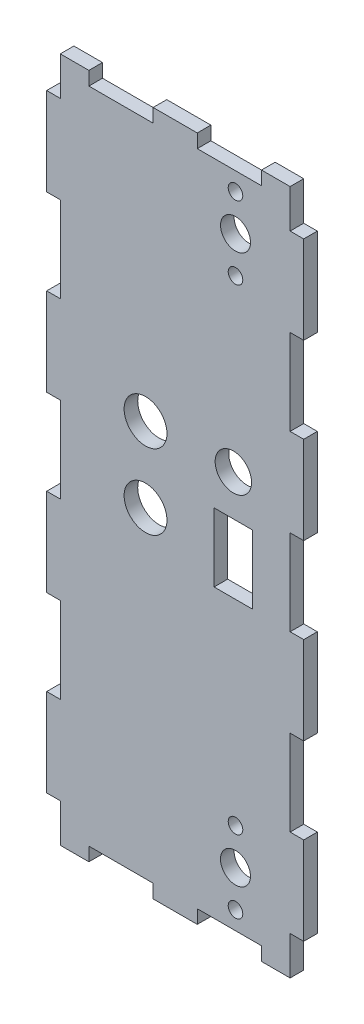
SolidWorks part; units mm, degrees
ref_plane "Front Plane" through (0, 0, 0) normal (0, 0, 1) x (1, 0, 0)
ref_plane "Top Plane" through (0, 0, 0) normal (0, 1, 0) x (1, 0, 0)
ref_plane "Right Plane" through (0, 0, 0) normal (1, 0, 0) x (0, 0, -1)
sketch "Sketch1" plane through (0, 0, 0) normal (0, 0, 1) x (1, 0, 0)
  line L1 (3.175, -25.5685) -> (-56.825, -25.5685)
  line L2 (3.175, -25.5685) -> (3.175, 134.4315)
  line L3 (3.175, 134.4315) -> (-56.825, 134.4315)
  line L4 (-56.825, -25.5685) -> (-56.825, 134.4315)
  dimension "D1" = 160
  dimension "D2" = 60
extrude "Boss-Extrude1" add sketch "Sketch1" against normal up to surface (3.175 mm away)
sketch "Sketch4" plane through (0, 0, 0) normal (0, 0, 1) x (1, 0, 0)
  line L0 (3.175, 134.4315) -> (-56.825, 134.4315) construction
  line L1 (-56.825, 134.4315) -> (-56.825, -25.5685) construction
  line L2 (-56.825, -25.5685) -> (3.175, -25.5685) construction
  line L3 (3.175, -25.5685) -> (0, -25.5685)
  line L4 (0, -25.5685) -> (0, -16.5685)
  line L5 (0, -16.5685) -> (3.175, -16.5685)
  line L6 (3.175, 3.9315) -> (0, 3.9315)
  line L7 (0, 24.1815) -> (0, 3.6815) construction
  line L8 (0, 3.9315) -> (0, 23.9315)
  line L9 (0, 23.9315) -> (3.175, 23.9315)
  line L10 (3.175, 44.4315) -> (0, 44.4315)
  line L11 (0, 64.6815) -> (0, 44.1815) construction
  line L12 (0, 44.4315) -> (0, 64.4315)
  line L13 (0, 64.4315) -> (3.175, 64.4315)
  line L14 (3.175, 84.9315) -> (0, 84.9315)
  line L15 (0, 105.1815) -> (0, 84.6815) construction
  line L16 (0, 84.9315) -> (0, 104.9315)
  line L17 (0, 104.9315) -> (3.175, 104.9315)
  line L18 (3.175, 125.4315) -> (0, 125.4315)
  line L19 (0, 134.4315) -> (0, 125.1815) construction
  line L40 (-31.975, -25.5685) -> (-46.975, -25.5685)
  line L41 (-31.975, -25.5685) -> (-31.975, -22.3935)
  line L42 (0, 125.4315) -> (0, 134.4315)
  line L43 (0, 134.4315) -> (3.175, 134.4315)
  line L45 (3.175, -25.5685) -> (3.175, -16.5685)
  line L46 (3.175, 125.4315) -> (3.175, 134.4315)
  line L47 (3.175, 84.9315) -> (3.175, 104.9315)
  line L48 (3.175, 44.4315) -> (3.175, 64.4315)
  line L49 (3.175, 3.9315) -> (3.175, 23.9315)
  line L58 (-26.825, 134.4315) -> (-26.825, -25.5685) construction
  line L59 (-56.825, 3.9315) -> (-56.825, 23.9315)
  line L60 (-56.825, 44.4315) -> (-56.825, 64.4315)
  line L61 (-56.825, 84.9315) -> (-56.825, 104.9315)
  line L62 (-56.825, 125.4315) -> (-56.825, 134.4315)
  line L63 (-56.825, -25.5685) -> (-56.825, -16.5685)
  line L64 (-53.65, 134.4315) -> (-56.825, 134.4315)
  line L65 (-53.65, 125.4315) -> (-53.65, 134.4315)
  line L66 (-56.825, 125.4315) -> (-53.65, 125.4315)
  line L67 (-53.65, 104.9315) -> (-56.825, 104.9315)
  line L68 (-53.65, 84.9315) -> (-53.65, 104.9315)
  line L69 (-56.825, 84.9315) -> (-53.65, 84.9315)
  line L70 (-53.65, 64.4315) -> (-56.825, 64.4315)
  line L71 (-53.65, 44.4315) -> (-53.65, 64.4315)
  line L72 (-56.825, 44.4315) -> (-53.65, 44.4315)
  line L73 (-53.65, 23.9315) -> (-56.825, 23.9315)
  line L74 (-53.65, 3.9315) -> (-53.65, 23.9315)
  line L75 (-56.825, 3.9315) -> (-53.65, 3.9315)
  line L76 (-53.65, -16.5685) -> (-56.825, -16.5685)
  line L77 (-53.65, -25.5685) -> (-53.65, -16.5685)
  line L78 (-56.825, -25.5685) -> (-53.65, -25.5685)
  line L79 (-31.975, -22.3935) -> (-46.975, -22.3935)
  line L80 (-46.975, -25.5685) -> (-46.975, -22.3935)
  line L81 (-6.675, -25.5685) -> (-6.675, -22.3935)
  line L82 (-21.675, -22.3935) -> (-6.675, -22.3935)
  line L83 (-21.675, -25.5685) -> (-21.675, -22.3935)
  line L84 (-21.675, -25.5685) -> (-6.675, -25.5685)
  line L86 (3.175, 54.4315) -> (-56.825, 54.4315) construction
  line L87 (-21.675, 134.4315) -> (-6.675, 134.4315)
  line L88 (-21.675, 134.4315) -> (-21.675, 131.2565)
  line L89 (-21.675, 131.2565) -> (-6.675, 131.2565)
  line L90 (-6.675, 134.4315) -> (-6.675, 131.2565)
  line L91 (-46.975, 134.4315) -> (-46.975, 131.2565)
  line L92 (-31.975, 131.2565) -> (-46.975, 131.2565)
  line L93 (-31.975, 134.4315) -> (-31.975, 131.2565)
  line L94 (-31.975, 134.4315) -> (-46.975, 134.4315)
  point P10 (3.175, 13.9315)
  point P11 (3.175, 54.4315)
  point P12 (3.175, 94.9315)
  point P69 (-56.825, 94.9315)
  point P70 (-56.825, 54.4315)
  point P71 (-56.825, 13.9315)
  dimension "D1" = 10
  dimension "D2" = 10
  dimension "D3" = 10
  dimension "D4" = 9
  dimension "D5" = 9
  dimension "D6" = 0
  dimension "D7" = 3.175
  dimension "D8" = 15
  dimension "D9" = 3.175
  dimension "D10" = 9.85
  dimension "D11" = 3.175
extrude "Cut-Extrude2" cut sketch "Sketch4" against normal up to surface (3.175 mm away) up to face at (-26.825, 54.4315, -3.175)
sketch "Sketch5" plane through (0, 0, 0) normal (0, 0, 1) x (1, 0, 0)
  line L1 (-6.675, -22.3935) -> (-21.675, -22.3935) construction
  line L2 (0, 23.9315) -> (0, 3.9315) construction
  line L3 (0, -16.5685) -> (0, -25.5685) construction
  line L4 (-9.25, -9.6435) -> (-16.25, -9.6435) construction
  line L5 (0, 54.4315) -> (-53.65, 54.4315) construction
  line L6 (0, 64.4315) -> (0, 44.4315) construction
  line L7 (-53.65, 44.4315) -> (-53.65, 64.4315) construction
  circle A0 centre (-12.75, -9.6435) radius 3.5
  circle A1 centre (-12.75, -18.1435) radius 1.7
  circle A2 centre (-12.75, -1.1435) radius 1.7
  circle A3 centre (-12.75, 127.0065) radius 1.7
  circle A4 centre (-12.75, 118.5065) radius 3.5
  circle A5 centre (-12.75, 110.0065) radius 1.7
  dimension "D1" = 7
  dimension "D5" = 3.4
  dimension "D2" = 12.75
  dimension "D3" = 12.75
  dimension "D4" = 8.5
  dimension "D6" = 12.75
extrude "Cut-Extrude3" cut sketch "Sketch5" against normal up to surface (3.175 mm away) up to face at (-26.825, 54.4315, -3.175)
sketch "Sketch6" plane through (0, 0, 0) normal (0, 0, 1) x (1, 0, 0)
  line L0 (-6.675, -22.3935) -> (-21.675, -22.3935) construction
  line L1 (-8.75, 44.6065) -> (-17.75, 44.6065)
  line L2 (-8.75, 44.6065) -> (-8.75, 60.6065)
  line L3 (-8.75, 60.6065) -> (-17.75, 60.6065)
  line L4 (-17.75, 44.6065) -> (-17.75, 60.6065)
  line L5 (0, 23.9315) -> (0, 3.9315) construction
  line L6 (-17.75, 52.6065) -> (-33.75, 52.6065) construction
  line L7 (-13.25, 60.6065) -> (-13.25, 70.1065) construction
  line L8 (-33.75, 52.6065) -> (-33.75, 70.1065) construction
  line L9 (-33.75, 70.1065) -> (-13.25, 70.1065) construction
  circle A1 centre (-33.75, 52.6065) radius 5
  circle A2 centre (-13.25, 70.1065) radius 4.25
  circle A3 centre (-33.75, 70.1065) radius 5
  dimension "D5" = 10
  dimension "D8" = 8.5
  dimension "D9" = 10
  dimension "D1" = 16
  dimension "D2" = 9
  dimension "D3" = 67
  dimension "D4" = 8.75
  dimension "D6" = 16
  dimension "D7" = 9.5
extrude "Cut-Extrude4" cut sketch "Sketch6" against normal up to surface (3.175 mm away) up to face at (-14.45, -18.1435, -3.175)
